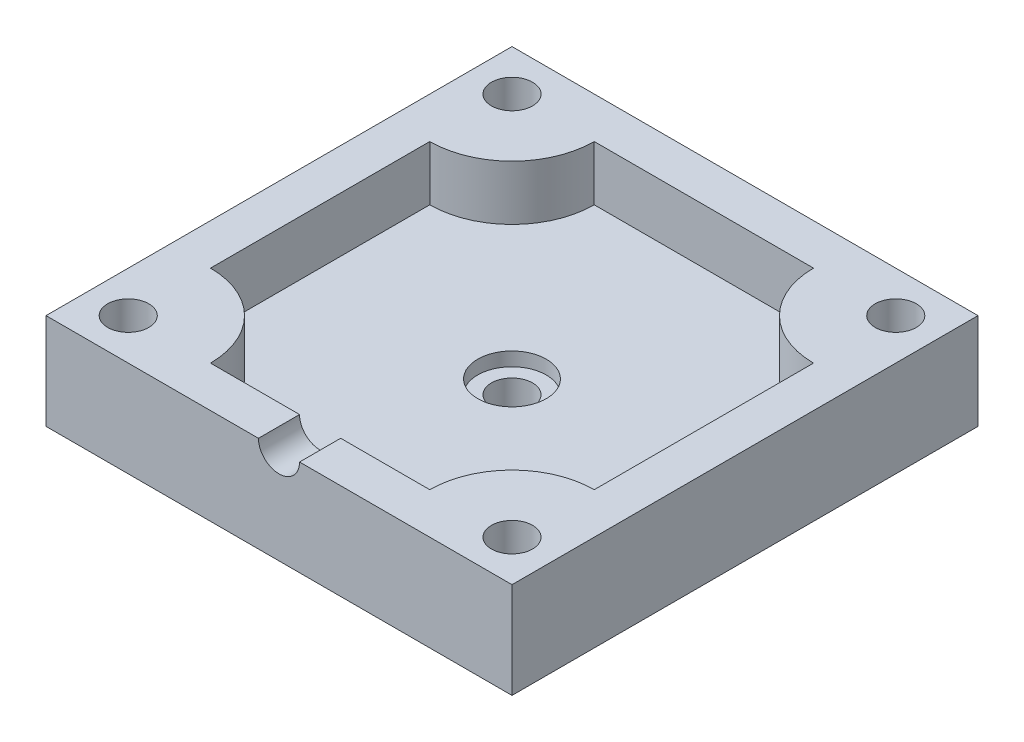
SolidWorks part; units mm, degrees
ref_plane "Front Plane" through (0, 0, 0) normal (0, 0, 1) x (1, 0, 0)
ref_plane "Top Plane" through (0, 0, 0) normal (0, 1, 0) x (1, 0, 0)
ref_plane "Right Plane" through (0, 0, 0) normal (1, 0, 0) x (0, 0, -1)
sketch "Sketch1" plane through (0, 0, 0) normal (0, 1, 0) x (1, 0, 0)
  line L1 (-17, 17) -> (17, 17)
  line L2 (-17, 17) -> (-17, -17)
  line L3 (-17, -17) -> (17, -17)
  line L4 (17, 17) -> (17, -17)
  line L5 (-17, 17) -> (17, -17) construction
  line L6 (-17, -17) -> (17, 17) construction
  point P0 (0, 0)
  dimension "D1" = 34
  dimension "D2" = 34
extrude "Boss-Extrude1" add sketch "Sketch1" along normal blind 7
sketch "Sketch2" plane through (0, 7, 0) normal (0, 1, 0) x (1, 0, 0)
  line L5 (8, 14) -> (-8, 14)
  line L6 (14, 8) -> (14, -8)
  line L7 (8, -14) -> (-8, -14)
  line L8 (-14, 8) -> (-14, -8)
  line L9 (14, 14) -> (-14, -14) construction
  line L10 (14, -14) -> (-14, 14) construction
  arc A5 (-14, 8) -> (-8, 14) centre (-14, 14) ccw
  arc A6 (8, 14) -> (14, 8) centre (14, 14) ccw
  arc A7 (14, -8) -> (8, -14) centre (14, -14) ccw
  arc A8 (-8, -14) -> (-14, -8) centre (-14, -14) ccw
  point P0 (0, 0)
  dimension "D3" = 12
  dimension "D1" = 28
  dimension "D2" = 28
extrude "Cut-Extrude1" cut sketch "Sketch2" against normal blind 4
sketch "Sketch3" plane through (0, 0, 17) normal (0, 0, 1) x (1, 0, 0)
  line L0 (-17, 7) -> (17, 7) construction
  circle A0 centre (0, 7) radius 1.5
  dimension "D1" = 3
extrude "Cut-Extrude2" cut sketch "Sketch3" against normal blind 10
sketch "Sketch4" plane through (0, 7, 0) normal (0, 1, 0) x (1, 0, 0)
  circle A1 centre (-14, 14) radius 1.5
  circle A2 centre (14, 14) radius 1.5
  circle A3 centre (14, -14) radius 1.5
  circle A4 centre (-14, -14) radius 1.5
  dimension "D1" = 3
extrude "Cut-Extrude3" cut sketch "Sketch4" against normal blind 10
sketch "Sketch5" plane through (0, 3, 0) normal (0, 1, 0) x (1, 0, 0)
  circle A0 centre (0, 0) radius 1.5
  dimension "D1" = 3
extrude "Cut-Extrude4" cut sketch "Sketch5" against normal blind 10
sketch "Sketch6" plane through (0, 3, 0) normal (0, 1, 0) x (1, 0, 0)
  circle A0 centre (0, 0) radius 2.5
  dimension "D1" = 5
extrude "Cut-Extrude5" cut sketch "Sketch6" against normal blind 1
